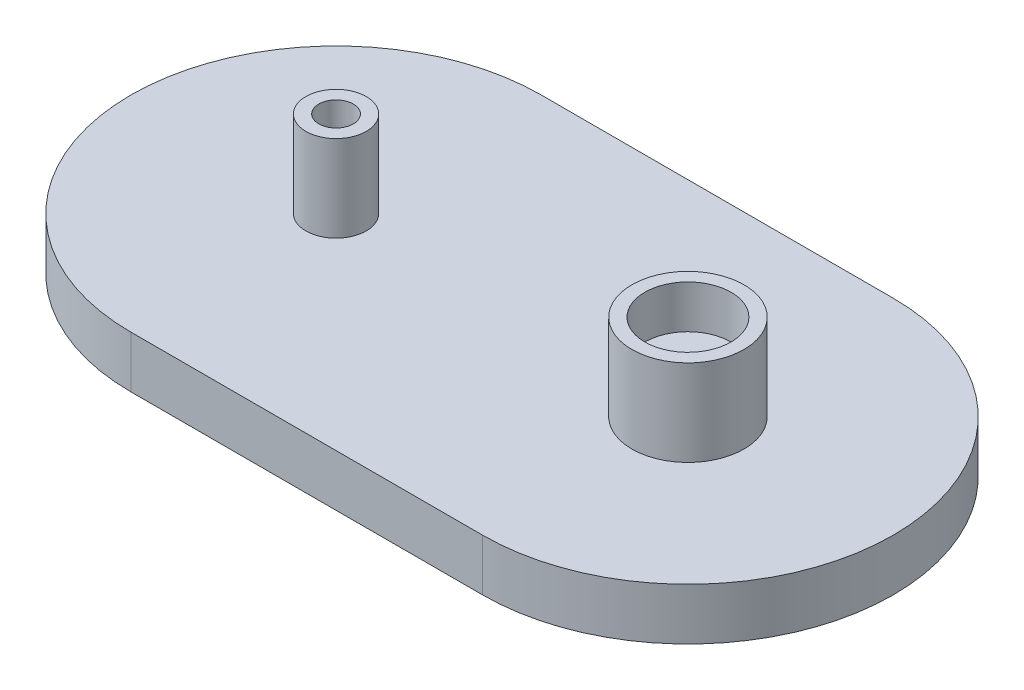
SolidWorks part; units mm, degrees
ref_plane "Plan de face" through (0, 0, 0) normal (0, 0, 1) x (1, 0, 0)
ref_plane "Plan de dessus" through (0, 0, 0) normal (0, 1, 0) x (1, 0, 0)
ref_plane "Plan de droite" through (0, 0, 0) normal (1, 0, 0) x (0, 0, -1)
sketch "Esquisse1" plane through (0, 0, 0) normal (0, 1, 0) x (1, 0, 0)
  line L0 (-16.5, 0) -> (17.7857, 0) construction
  line L1 (0, 17.5357) -> (0, -17.8929) construction
  line L2 (10.2, 0) -> (-10.2, 0) construction
  line L3 (10.2, -11.9) -> (-10.2, -11.9)
  line L4 (10.2, 11.9) -> (-10.2, 11.9)
  arc A0 (10.2, -11.9) -> (10.2, 11.9) centre (10.2, 0) ccw
  arc A1 (-10.2, 11.9) -> (-10.2, -11.9) centre (-10.2, 0) ccw
  point P7 (0, 0)
  dimension "D1" = 10.2
  dimension "D2" = 23.8
extrude "Boss.-Extru.1" add sketch "Esquisse1" along normal blind 3
sketch "Esquisse2" plane through (0, 3, 0) normal (0, 1, 0) x (1, 0, 0)
  line L2 (10.2, 11.9) -> (-10.2, 11.9)
  line L3 (-10.2, -11.9) -> (10.2, -11.9)
  line L4 (10.2, 11.9) -> (-10.2, 11.9)
  line L5 (-10.2, -11.9) -> (10.2, -11.9)
  circle A0 centre (-10.2, 0) radius 1.75
  circle A1 centre (10.2, 0) radius 3.25
  arc A2 (10.2, -11.9) -> (10.2, 11.9) centre (10.2, 0) ccw
  arc A3 (-10.2, 11.9) -> (-10.2, -11.9) centre (-10.2, 0) ccw
  arc A4 (10.2, -11.9) -> (10.2, 11.9) centre (10.2, 0) ccw
  arc A5 (-10.2, 11.9) -> (-10.2, -11.9) centre (-10.2, 0) ccw
  dimension "D2" = 6.5
  dimension "D3" = 3.5
  dimension "D1" = 0
extrude "Boss.-Extru.2" add sketch "Esquisse2" along normal blind 5 contours A0 | A1
sketch "Esquisse3" plane through (0, 8, 0) normal (0, 1, 0) x (1, 0, 0)
  circle A0 centre (10.2, 0) radius 3.25 construction
  circle A1 centre (-10.2, 0) radius 1.75
  circle A2 centre (-10.2, 0) radius 1.75
  circle A3 centre (10.2, 0) radius 3.25
  circle A4 centre (-10.2, 0) radius 1
  circle A5 centre (10.2, 0) radius 2.5
  dimension "D2" = 2
  dimension "D3" = 5
  dimension "D1" = 0
extrude "Enlèv. mat.-Extru.1" cut sketch "Esquisse3" against normal blind 2.5 contours A5 | A4
